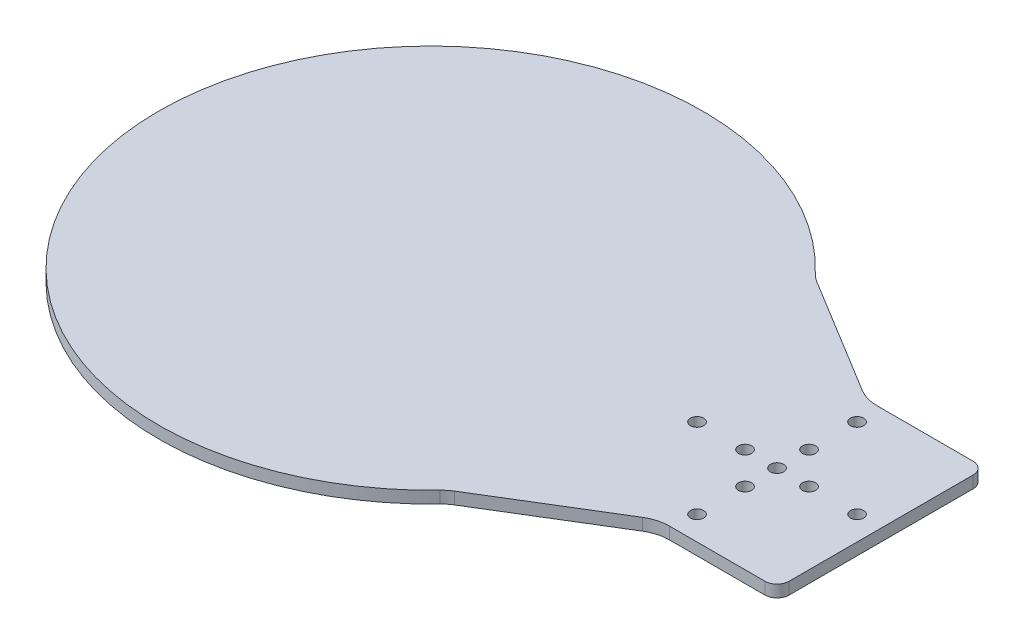
SolidWorks part; units mm, degrees
ref_plane "Front Plane" through (0, 0, 0) normal (0, 0, 1) x (1, 0, 0)
ref_plane "Top Plane" through (0, 0, 0) normal (0, 1, 0) x (1, 0, 0)
ref_plane "Right Plane" through (0, 0, 0) normal (1, 0, 0) x (0, 0, -1)
sketch "Sketch1" plane through (0, 0, 0) normal (0, 1, 0) x (1, 0, 0)
  line L0 (0, 0) -> (162.6239, 0) construction
  line L1 (62.8331, -26) -> (112.579, -26)
  line L2 (112.579, -26) -> (112.579, 26)
  line L3 (62.8331, 26) -> (112.579, 26)
  arc A0 (62.8331, 26) -> (62.8331, -26) centre (0, 0) ccw
  circle A1 centre (86.579, 0) radius 1.65
  circle A2 centre (94.579, 0) radius 1.65
  circle A3 centre (106.579, 0) radius 1.65
  circle A4 centre (86.579, -8) radius 1.65
  circle A5 centre (86.579, -20) radius 1.65
  circle A6 centre (78.579, 0) radius 1.65
  circle A7 centre (66.579, 0) radius 1.65
  circle A8 centre (86.579, 8) radius 1.65
  circle A9 centre (86.579, 20) radius 1.65
  point P24 (86.579, 0)
  point P28 (112.579, 0)
  dimension "D1" = 136
  dimension "D3" = 3.3
  dimension "D5" = 3.3
  dimension "D2" = 86.579
  dimension "D4" = 8
  dimension "D8" = 6
  dimension "D9" = 6
  dimension "D6" = 2
  dimension "D7" = 4
extrude "Boss-Extrude1" add sketch "Sketch1" along normal blind 3
sketch "Sketch2" plane through (0, 3, 0) normal (0, 1, 0) x (1, 0, 0)
  line L1 (112.579, 26) -> (62.8331, 26) construction
  line L3 (82.8331, 26) -> (62.8331, 26)
  line L4 (50.0799, 46) -> (82.8331, 26)
  line L5 (0, 0) -> (38.3553, 0) construction
  line L6 (50.0799, -46) -> (82.8331, -26)
  line L7 (82.8331, -26) -> (62.8331, -26)
  arc A0 (62.8331, 26) -> (62.8331, -26) centre (0, 0) ccw construction
  arc A1 (62.8331, 26) -> (50.0799, 46) centre (0, 0) ccw
  arc A2 (62.8331, -26) -> (50.0799, -46) centre (0, 0) cw
  point P10 (40.2989, -51)
  arc M9 (62.8331, 26) -> (62.8331, -26) centre (0, 0) ccw
  line M10 (62.8331, -26) -> (112.579, -26)
  line M12 (112.579, 26) -> (62.8331, 26)
  dimension "D1" = 20
  dimension "D2" = 20
extrude "Boss-Extrude2" add sketch "Sketch2" against normal blind 3 contours L6 M9 M10 | L4 M9 M12
fillet "Fillet1" radius 10 4 edges at (82.8331, 1.5, 26) (50.0799, 1.5, 46) (50.0799, 1.5, -46) (82.8331, 1.5, -26)
fillet "Fillet2" radius 3 2 edges at (112.579, 1.5, -26) (112.579, 1.5, 26)
